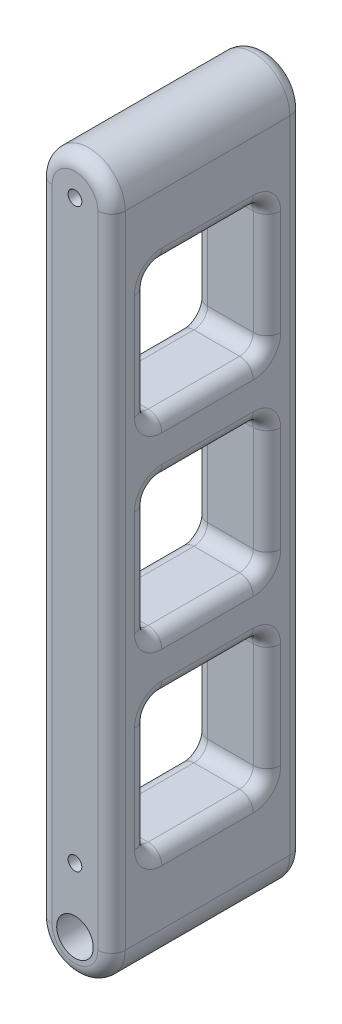
SolidWorks part; units mm, degrees
material "ABS PC"
ref_plane "Front Plane" through (0, 0, 0) normal (0, 0, 1) x (1, 0, 0)
ref_plane "Top Plane" through (0, 0, 0) normal (0, 1, 0) x (1, 0, 0)
ref_plane "Right Plane" through (0, 0, 0) normal (1, 0, 0) x (0, 0, -1)
sketch "Sketch1" plane through (0, 0, 0) normal (0, 0, 1) x (1, 0, 0)
  line L1 (8, 0) -> (8, 140)
  line L2 (-8, 0) -> (-8, 140)
  circle A0 centre (0, 0) radius 4
  arc A1 (-8, 0) -> (8, 0) centre (0, 0) ccw
  arc A2 (8, 140) -> (-8, 140) centre (0, 140) ccw
  circle A3 centre (0, 140) radius 1.5
  dimension "D2" = 8
  dimension "D3" = 16
  dimension "D4" = 3
  dimension "D1" = 8
  dimension "D5" = 140
extrude "Boss-Extrude1" add sketch "Sketch1" along normal blind 42
sketch "Sketch6" plane through (-8, 0, 0) normal (-1, 0, 0) x (0, 0, 1)
  line L1 (8, 126) -> (34, 126)
  line L2 (8, 126) -> (8, 97)
  line L3 (8, 97) -> (34, 97)
  line L4 (34, 126) -> (34, 97)
  line L5 (34, 85) -> (8, 85)
  line L6 (34, 85) -> (34, 56)
  line L7 (34, 56) -> (8, 56)
  line L8 (8, 85) -> (8, 56)
  line L9 (8, 44) -> (34, 44)
  line L10 (8, 44) -> (8, 15)
  line L11 (8, 15) -> (34, 15)
  line L12 (34, 44) -> (34, 15)
extrude "Cut-Extrude4" cut sketch "Sketch6" against normal through all both and the other way through all
ref_plane "Plane1" through (0, 150, 0) normal (0, 1, 0) x (1, 0, 0)
ref_plane "Plane2" through (0, 0, 36) normal (0, 0, 1) x (1, 0, 0)
sketch "Sketch5" plane through (0, 0, 42) normal (0, 0, 1) x (1, 0, 0)
  circle A0 centre (0, 14) radius 1.5
  point P2 (0, 0)
  dimension "D1" = 3
  dimension "D2" = 14
extrude "Cut-Extrude3" cut sketch "Sketch5" against normal blind 6
fillet "Fillet5" radius 3 44 edges at (0, -8, 42) (-8, 70, 42) (0, 148, 42) (0, -8, 0) (-8, 70, 0) (0, 148, 0) (8, 70, 0) (8, 70, 42) (-8, 29.5, 34) (-8, 29.5, 8) (8, 29.5, 8) (8, 29.5, 34) (-8, 70.5, 34) (-8, 70.5, 8) (8, 70.5, 8) (8, 70.5, 34) (8, 111.5, 34) (8, 111.5, 8) (-8, 44, 21) (0, 44, 34) (8, 44, 21) (0, 44, 8) (-8, 85, 21) (0, 85, 34) (8, 85, 21) (0, 85, 8) (-8, 15, 21) (0, 15, 8) (8, 15, 21) (0, 15, 34) (-8, 56, 21) (0, 56, 8) (8, 56, 21) (0, 56, 34) (0, 97, 8) (8, 97, 21) (0, 97, 34) (0, 126, 34) (8, 126, 21) (0, 126, 8) (-8, 111.5, 8) (-8, 97, 21) (-8, 111.5, 34) (-8, 126, 21)
